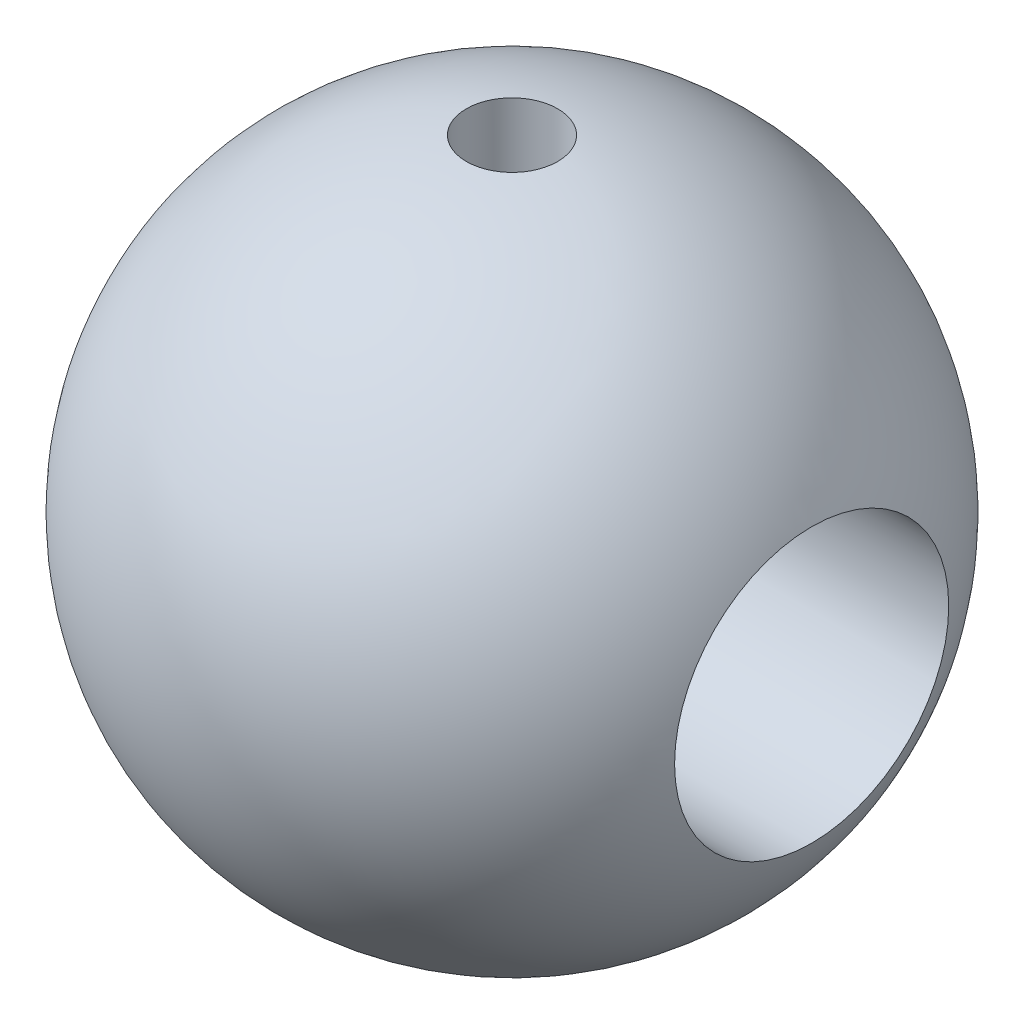
SolidWorks part; units mm, degrees
ref_plane "Front" through (0, 0, 0) normal (0, 0, 1) x (1, 0, 0)
ref_plane "Top" through (0, 0, 0) normal (0, 1, 0) x (1, 0, 0)
ref_plane "Right" through (0, 0, 0) normal (1, 0, 0) x (0, 0, -1)
sketch "Sketch1" plane through (0, 0, 0) normal (0, 0, 1) x (1, 0, 0)
  line L0 (-12.6822, 0) -> (12.6822, 0) construction
  line L1 (-9.525, 0) -> (9.525, 0)
  arc A0 (9.525, 0) -> (-9.525, 0) centre (0, 0) ccw
  point P6 (0, 0)
  dimension "D1" = 19.05
revolve "Revolve1" add sketch "Sketch1" angle 360 about L0
sketch "Sketch2" plane through (0, 0, 0) normal (1, 0, 0) x (0, 0, -1)
  circle A0 centre (0, 0) radius 3.9624
  dimension "D1" = 7.9248
extrude "Cut-Extrude1" cut sketch "Sketch2" against normal up to next and the other way up to next
ref_plane "Plane1" through (0, 9.525, 0) normal (0, 1, 0) x (1, 0, 0)
hole_wizard "#37 (0.104) Diameter Hole1" positions "Sketch5" profile "Sketch6" hole size "#37" standard "ANSI Inch" end condition through all
sketch "Sketch5" plane through (0, 9.525, 0) normal (0, 1, 0) x (1, 0, 0)
  point P0 (0, 0)
sketch "Sketch6" plane through (0, 9.525, 0) normal (1, 0, 0) x (0, 0, 1)
  line L0 (0, 0) -> (0, 19.05)
  line L1 (0, 19.05) -> (1.3208, 19.05)
  line L2 (1.3208, 19.05) -> (1.3208, 0)
  line L5 (1.3208, 0) -> (0, 0)
  line L11 (0, -6.35) -> (0, 107.95) construction
  dimension "Thru Hole Dia." = 2.6416
  dimension "Thru Hole Depth" = 19.05
ref_plane "Plane2" through (9.525, 0, 0) normal (1, 0, 0) x (0, 0, -1)
ref_plane "Plane3" through (-9.525, 0, 0) normal (1, 0, 0) x (0, 0, -1)
